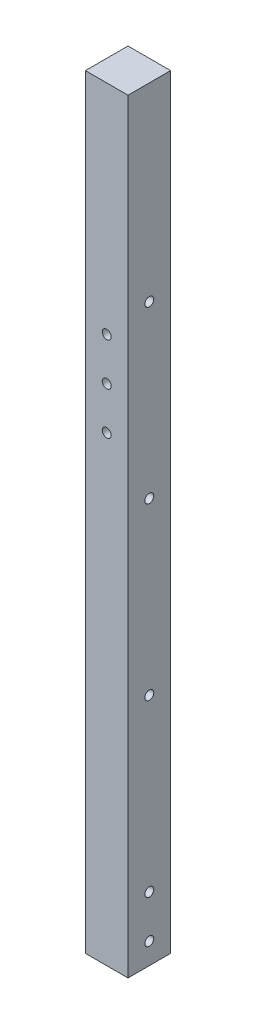
SolidWorks part; units mm, degrees
ref_plane "前视基准面" through (0, 0, 0) normal (0, 0, 1) x (1, 0, 0)
ref_plane "上视基准面" through (0, 0, 0) normal (0, 1, 0) x (1, 0, 0)
ref_plane "右视基准面" through (0, 0, 0) normal (1, 0, 0) x (0, 0, -1)
sketch "草图1" plane through (0, 0, 0) normal (0, 1, 0) x (1, 0, 0)
  line L1 (-10, 10) -> (10, 10)
  line L2 (-10, 10) -> (-10, -10)
  line L3 (-10, -10) -> (10, -10)
  line L4 (10, 10) -> (10, -10)
  line L5 (-10, 10) -> (10, -10) construction
  line L6 (-10, -10) -> (10, 10) construction
  point P0 (0, 0)
  dimension "D1" = 20
  dimension "D2" = 20
extrude "凸台-拉伸1" add sketch "草图1" along normal blind 358.95
sketch "草图2" plane through (10, 0, 0) normal (1, 0, 0) x (0, 0, -1)
  line L0 (-10, 0) -> (10, 0) construction
  line L1 (-10, 358.95) -> (-10, 0) construction
  circle A0 centre (0, 10) radius 2.1
  circle A1 centre (0, 30) radius 2.1
  circle A2 centre (0, 110) radius 2.1
  circle A3 centre (0, 190) radius 2.1
  circle A4 centre (0, 270) radius 2.1
  dimension "D1" = 4.2
  dimension "D2" = 4.2
  dimension "D7" = 80
  dimension "D3" = 10
  dimension "D4" = 20
  dimension "D5" = 10
  dimension "D6" = 4
extrude "切除-拉伸1" cut sketch "草图2" against normal through all
sketch "草图3" plane through (0, 0, -10) normal (0, 0, -1) x (-1, 0, 0)
  line L0 (-10, 358.95) -> (-10, 0) construction
  line L1 (-10, 0) -> (10, 0) construction
  circle A0 centre (0, 216.69) radius 2.1
  circle A1 centre (0, 236.69) radius 2.1
  circle A2 centre (0, 256.69) radius 2.1
  dimension "D1" = 4.2
  dimension "D2" = 10
  dimension "D3" = 216.69
  dimension "D5" = 20
  dimension "D4" = 3
extrude "切除-拉伸2" cut sketch "草图3" against normal through all
